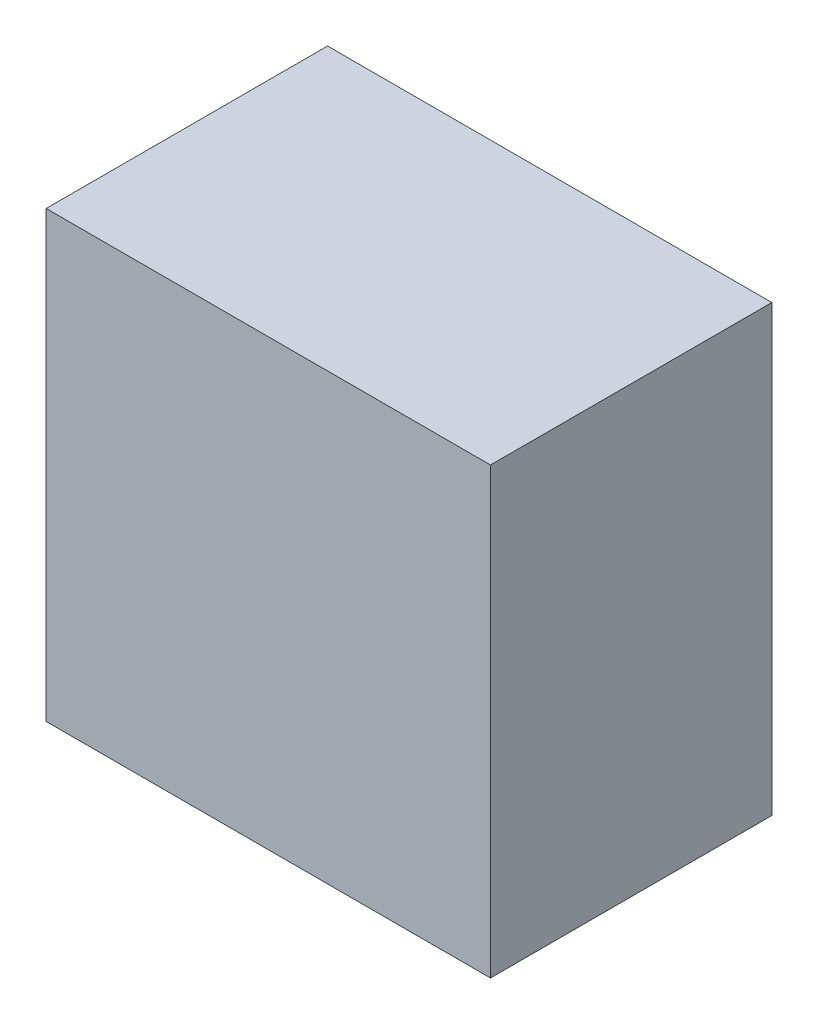
SolidWorks part; units mm, degrees
material "ABS"
ref_plane "X-Y Datum" through (0, 0, 0) normal (0, 0, 1) x (1, 0, 0)
ref_plane "X-Z Datum" through (0, 0, 0) normal (0, 1, 0) x (1, 0, 0)
ref_plane "Y-Z Datum" through (0, 0, 0) normal (1, 0, 0) x (0, 0, -1)
sketch "Sketch1" plane through (0, 0, 0) normal (0, 0, 1) x (1, 0, 0)
  line L1 (-30, -30) -> (30, -30)
  line L2 (-30, -30) -> (-30, 30)
  line L3 (-30, 30) -> (30, 30)
  line L4 (30, -30) -> (30, 30)
  line L5 (-30, -30) -> (30, 30) construction
  line L6 (-30, 30) -> (30, -30) construction
  point P0 (0, 0)
extrude "Boss-Extrude1" add sketch "Sketch1" along normal blind 38
